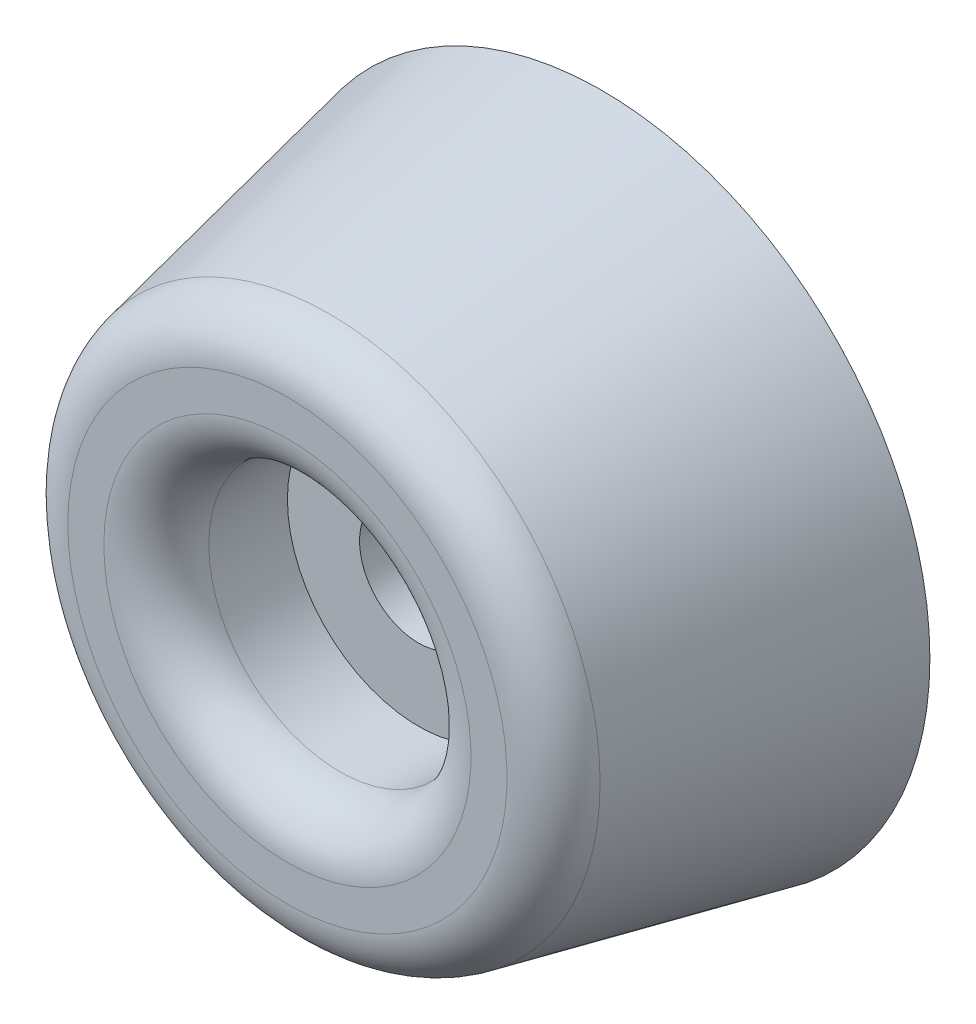
SolidWorks part; units mm, degrees
material "POLYURETHANE (11671)"
ref_plane "Face" through (0, 0, 0) normal (0, 0, 1) x (1, 0, 0)
ref_plane "Dessus" through (0, 0, 0) normal (0, 1, 0) x (1, 0, 0)
ref_plane "Droite" through (0, 0, 0) normal (1, 0, 0) x (0, 0, -1)
sketch "Esquisse1" plane through (0, 0, 0) normal (1, 0, 0) x (0, 0, -1)
  line L0 (0, 0) -> (12, 0)
  line L1 (12, 0) -> (12, 12.5)
  line L2 (12, 12.5) -> (0, 10)
  line L3 (0, 10) -> (0, 0)
  dimension "D1" = 12
  dimension "D2" = 12.5
  dimension "D3" = 10
revolve "Révolution1" add sketch "Esquisse1" angle 360 about L0
sketch "Esquisse2" plane through (0, 0, 0) normal (0, 0, 1) x (1, 0, 0)
  circle A0 centre (0, 0) radius 2.25
extrude "Enlèv. mat.-Extru.1" cut sketch "Esquisse2" against normal up to next
sketch "Esquisse3" plane through (0, 0, 0) normal (0, 0, 1) x (1, 0, 0)
  circle A0 centre (0, 0) radius 5
extrude "Enlèv. mat.-Extru.2" cut sketch "Esquisse3" against normal blind 5
fillet "Congé1" radius 2 2 edges at (10, 0, 0) (5, 0, 0)
